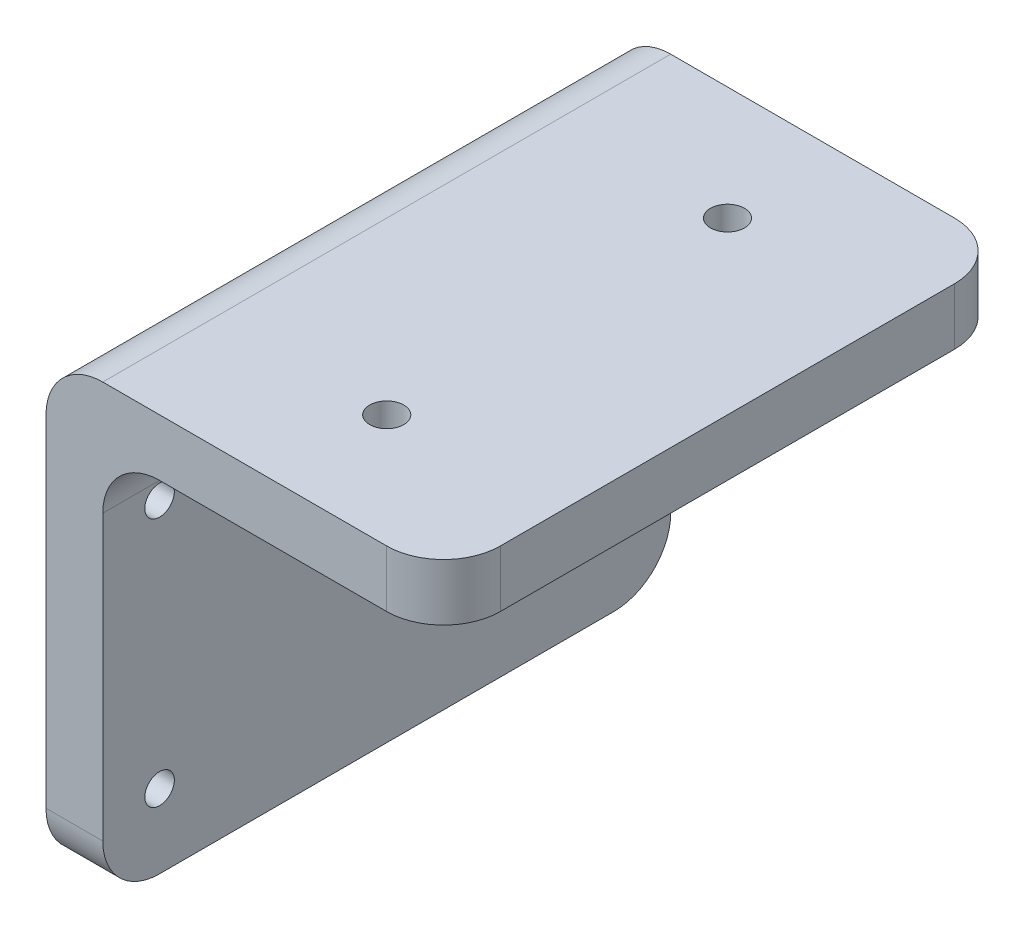
SolidWorks part; units mm, degrees
material "ABS"
ref_plane "Plan de face" through (0, 0, 0) normal (0, 0, 1) x (1, 0, 0)
ref_plane "Plan de dessus" through (0, 0, 0) normal (0, 1, 0) x (1, 0, 0)
ref_plane "Plan de droite" through (0, 0, 0) normal (1, 0, 0) x (0, 0, -1)
sketch "Esquisse1" plane through (0, 0, 0) normal (0, 1, 0) x (1, 0, 0)
  line L1 (15, -25) -> (-15, -25)
  line L2 (15, -25) -> (15, 25)
  line L3 (15, 25) -> (-15, 25)
  line L4 (-15, -25) -> (-15, 25)
  point P4 (0, 25)
  point P6 (15, 0)
  dimension "D1" = 30
  dimension "D2" = 50
extrude "Boss.-Extru.1" add sketch "Esquisse1" against normal blind 5
sketch "Esquisse2" plane through (-15, 0, 0) normal (-1, 0, 0) x (0, 0, 1)
  line L1 (25, 0) -> (-25, 0)
  line L2 (25, 0) -> (25, -40)
  line L3 (25, -40) -> (-25, -40)
  line L4 (-25, 0) -> (-25, -40)
  line L7 (-25, 0) -> (25, 0) construction
  line L8 (-25, -5) -> (-25, 0) construction
  dimension "D1" = 50
  dimension "D2" = 40
extrude "Boss.-Extru.2" add sketch "Esquisse2" along normal blind 5
fillet "Congé2" radius 5 6 edges at (15, -2.5, -25) (-20, 0, 0) (-17.5, -40, -25) (15, -2.5, 25) (-17.5, -40, 25) (-15, -5, 0)
sketch "Esquisse11" plane through (0, 0, 0) normal (0, 1, 0) x (1, 0, 0)
  circle A0 centre (0, 15) radius 1.5
  circle A1 centre (0, -15) radius 1.5
  dimension "D1" = 3
  dimension "D2" = 3
  dimension "D3" = 15
  dimension "D4" = 15
extrude "Enlèv. mat.-Extru.2" cut sketch "Esquisse11" against normal through all
sketch "Esquisse12" plane through (-20, 0, 0) normal (-1, 0, 0) x (0, 0, 1)
  circle A0 centre (-12, -22.5) radius 10.25
  circle A1 centre (-20, -11.5) radius 1.3
  circle A2 centre (-20, -33.5) radius 1.3
  circle A3 centre (20, -33.5) radius 1.3
  circle A4 centre (20, -11.5) radius 1.3
  dimension "D1" = 20.5
  dimension "D4" = 2.6
  dimension "D5" = 2.6
  dimension "D6" = 2.6
  dimension "D7" = 2.6
  dimension "D2" = 12
  dimension "D3" = 22.5
  dimension "D8" = 8
  dimension "D9" = 11
  dimension "D10" = 22
  dimension "D11" = 40
extrude "Enlèv. mat.-Extru.3" cut sketch "Esquisse12" against normal through all
